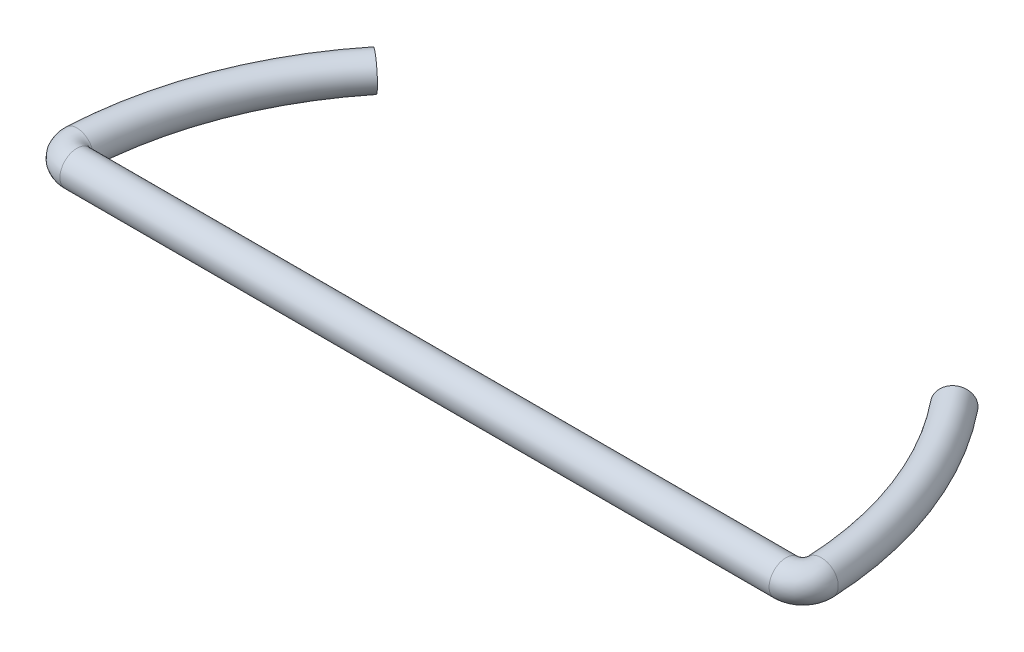
SolidWorks part; units mm, degrees
ref_plane "Front Plane" through (0, 0, 0) normal (0, 0, 1) x (1, 0, 0)
ref_plane "Top Plane" through (0, 0, 0) normal (0, 1, 0) x (1, 0, 0)
ref_plane "Right Plane" through (0, 0, 0) normal (1, 0, 0) x (0, 0, -1)
sketch "Sketch1" plane through (0, 0, 0) normal (0, 1, 0) x (1, 0, 0)
  line L0 (31.4643, 0) -> (-31.4643, 0)
  arc A0 (27.129, -18.7887) -> (32.9626, -1.5714) centre (0, 0) ccw
  arc A1 (-25.7085, 20.6899) -> (-32.9626, 1.5714) centre (0, 0) ccw
  arc A2 (31.4643, 0) -> (32.9626, -1.5714) centre (31.4643, -1.5) cw
  arc A3 (-31.4643, 0) -> (-32.9626, 1.5714) centre (-31.4643, 1.5) cw
  point P9 (33, 0)
  point P12 (-33, 0)
  dimension "D2" = 1.5
  dimension "D1" = 66
sketch "Sketch2" plane through (0, 0, 0) normal (1, 0, 0) x (0, 0, -1)
  circle A0 centre (0, 0) radius 1.5
  dimension "D1" = 3
sweep "Sweep1" add profiles "Sketch2" path "Sketch1"
mirror "Mirror1" about plane through (0, 0, 0) normal (1, 0, 0) of "Sweep1"
